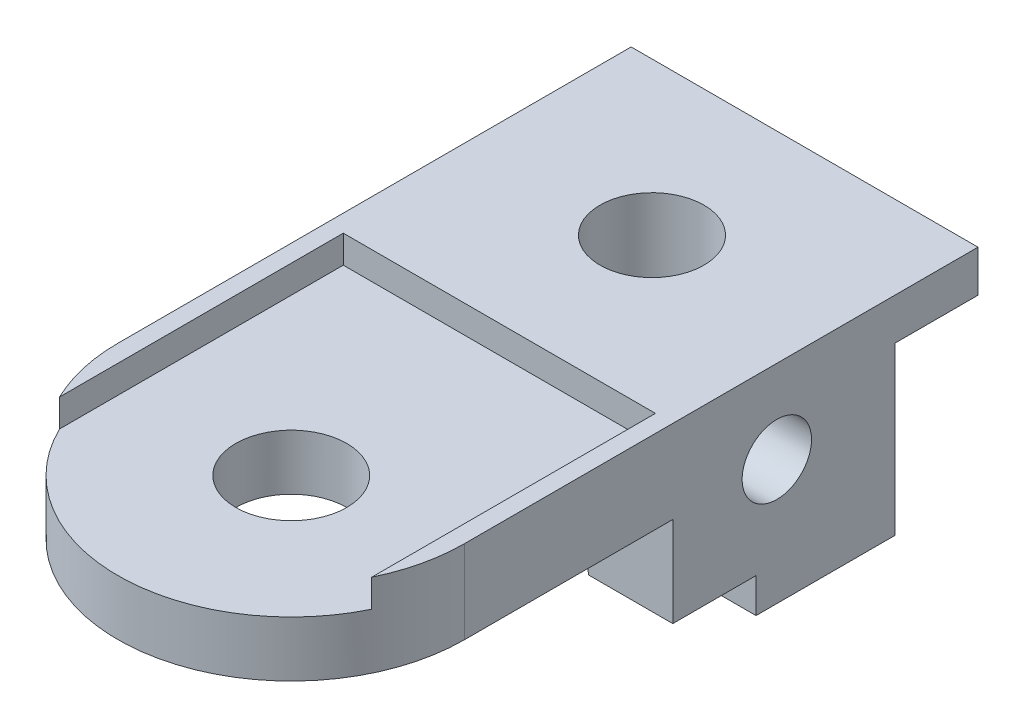
SolidWorks part; units mm, degrees
ref_plane "Plan de face" through (0, 0, 0) normal (0, 0, 1) x (1, 0, 0)
ref_plane "Plan de dessus" through (0, 0, 0) normal (0, 1, 0) x (1, 0, 0)
ref_plane "Plan de droite" through (0, 0, 0) normal (1, 0, 0) x (0, 0, -1)
sketch "Esquisse1" plane through (0, 0, 0) normal (0, 1, 0) x (1, 0, 0)
  line L0 (-25, 0) -> (-25, 30)
  line L1 (-25, 30) -> (25, 30)
  line L2 (25, 30) -> (25, 0)
  arc A0 (25, 0) -> (-25, 0) centre (0, 0) cw
  dimension "D1" = 25
  dimension "D2" = 30
extrude "Boss.-Extru.1" add sketch "Esquisse1" against normal blind 12
sketch "Esquisse2" plane through (0, 0, 0) normal (0, 1, 0) x (1, 0, 0)
  line L1 (25, 30) -> (-25, 30) construction
  line L2 (-22.5, 30) -> (22.5, 30)
  line L3 (22.5, 30) -> (22.5, -10.8972)
  line L4 (-22.5, 30) -> (-22.5, -10.8972)
  arc A1 (-25, 0) -> (25, 0) centre (0, 0) ccw construction
  arc A2 (-22.5, -10.8972) -> (22.5, -10.8972) centre (0, 0) ccw
  point P8 (0, 0)
  dimension "D1" = 45
extrude "Enlèv. mat.-Extru.1" cut sketch "Esquisse2" against normal blind 4
sketch "Esquisse3" plane through (0, -12, 0) normal (0, -1, 0) x (1, 0, 0)
  line L0 (25, -30) -> (-25, -30) construction
  circle A0 centre (0, 0) radius 8
  dimension "D2" = 16
  dimension "D1" = 30
extrude "Enlèv. mat.-Extru.2" cut sketch "Esquisse3" against normal through all
sketch "Esquisse4" plane through (0, 0, 0) normal (0, 1, 0) x (1, 0, 0)
  line L1 (-25, 42) -> (25, 42)
  line L2 (-25, 42) -> (-25, 30)
  line L3 (-25, 30) -> (25, 30)
  line L4 (25, 42) -> (25, 30)
  line L5 (-25, 42) -> (25, 30) construction
  line L6 (-25, 30) -> (25, 42) construction
  point P0 (0, 36)
  point P6 (-41.0373, 42)
  point P7 (0, 0)
  point P8 (0, 0)
  dimension "D1" = 12
extrude "Boss.-Extru.2" add sketch "Esquisse4" against normal blind 25
sketch "Esquisse5" plane through (0, 0, -30) normal (0, 0, 1) x (1, 0, 0)
  line L11 (-25, -25) -> (25, -25) construction
  line L12 (12.8348, -25) -> (-12.8348, -25)
  arc A2 (-12.8348, -25) -> (12.8348, -25) centre (0, -25) cw
  dimension "D1" = 12.8348
extrude "Enlèv. mat.-Extru.3" cut sketch "Esquisse5" against normal through all
sketch "Esquisse7" plane through (0, 0, 0) normal (0, 1, 0) x (1, 0, 0)
  line L1 (-25, 62) -> (25, 62)
  line L2 (-25, 62) -> (-25, 42)
  line L3 (-25, 42) -> (25, 42)
  line L4 (25, 62) -> (25, 42)
  line L5 (-25, 62) -> (25, 42) construction
  line L6 (-25, 42) -> (25, 62) construction
  point P0 (0, 52)
  point P6 (-20.061, 53.3504)
  point P7 (0, 0)
  point P8 (0, 0)
  point P9 (0, 0)
  dimension "D1" = 20
extrude "Boss.-Extru.3" add sketch "Esquisse7" against normal blind 30
sketch "Esquisse9" plane through (0, 0, 0) normal (0, 1, 0) x (1, 0, 0)
  line L0 (25, 62) -> (-25, 62) construction
  line L1 (-25, 74) -> (25, 74)
  line L2 (-25, 74) -> (-25, 62)
  line L3 (-25, 62) -> (25, 62)
  line L4 (25, 74) -> (25, 62)
  line L5 (-25, 74) -> (25, 62) construction
  line L6 (-25, 62) -> (25, 74) construction
  point P0 (0, 68)
  point P6 (-22.8606, 62)
  dimension "D1" = 12
extrude "Boss.-Extru.4" add sketch "Esquisse9" against normal blind 6
sketch "Esquisse10" plane through (25, 0, 0) normal (1, 0, 0) x (0, 0, -1)
  line L0 (30, -25) -> (30, -12) construction
  line L2 (0, 0) -> (74, 0) construction
  circle A0 centre (45, -12) radius 5
  point P6 (47.6701, 0)
  dimension "D3" = 10
  dimension "D1" = 15
  dimension "D2" = 12
extrude "Enlèv. mat.-Extru.4" cut sketch "Esquisse10" against normal through all
sketch "Esquisse11" plane through (0, -30, 0) normal (0, -1, 0) x (1, 0, 0)
  line L0 (25, -62) -> (-25, -62) construction
  line L2 (25, -42) -> (25, -62) construction
  circle A0 centre (0, -52) radius 7.5
  point P2 (0, 0)
  point P5 (0, 0)
  point P8 (25, -49.6156)
  dimension "D1" = 15
  dimension "D2" = 10
  dimension "D3" = 25
extrude "Enlèv. mat.-Extru.5" cut sketch "Esquisse11" against normal through all
